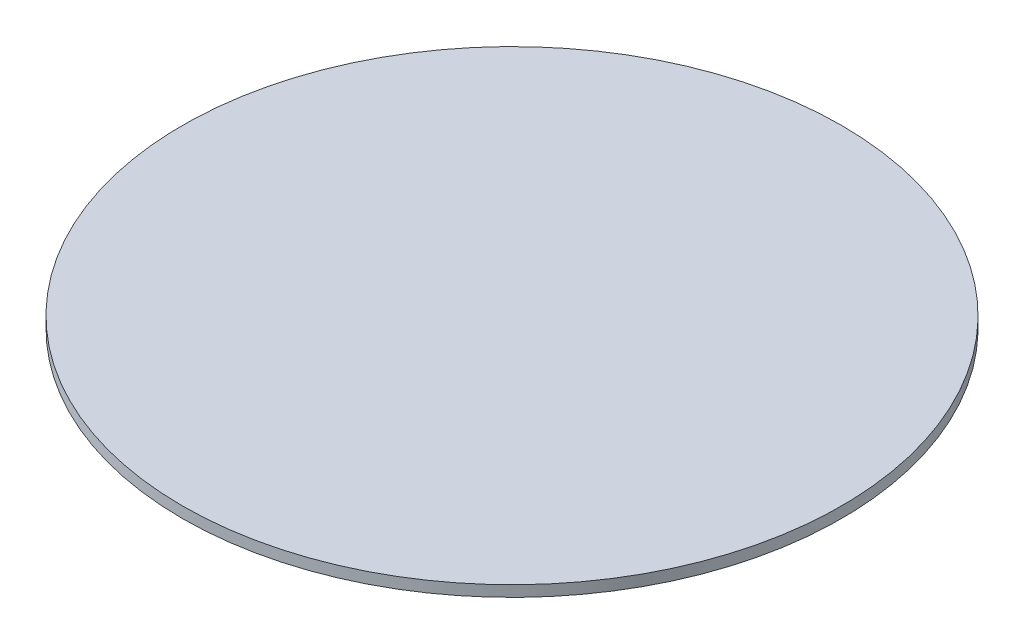
SolidWorks part; units mm, degrees
ref_plane "前视基准面" through (0, 0, 0) normal (0, 0, 1) x (1, 0, 0)
ref_plane "上视基准面" through (0, 0, 0) normal (0, 1, 0) x (1, 0, 0)
ref_plane "右视基准面" through (0, 0, 0) normal (1, 0, 0) x (0, 0, -1)
sketch "草图1" plane through (0, 0, 0) normal (0, 1, 0) x (1, 0, 0)
  circle A0 centre (0, 0) radius 30
  dimension "D1" = 60
extrude "凸台-拉伸1" add sketch "草图1" along normal blind 1
